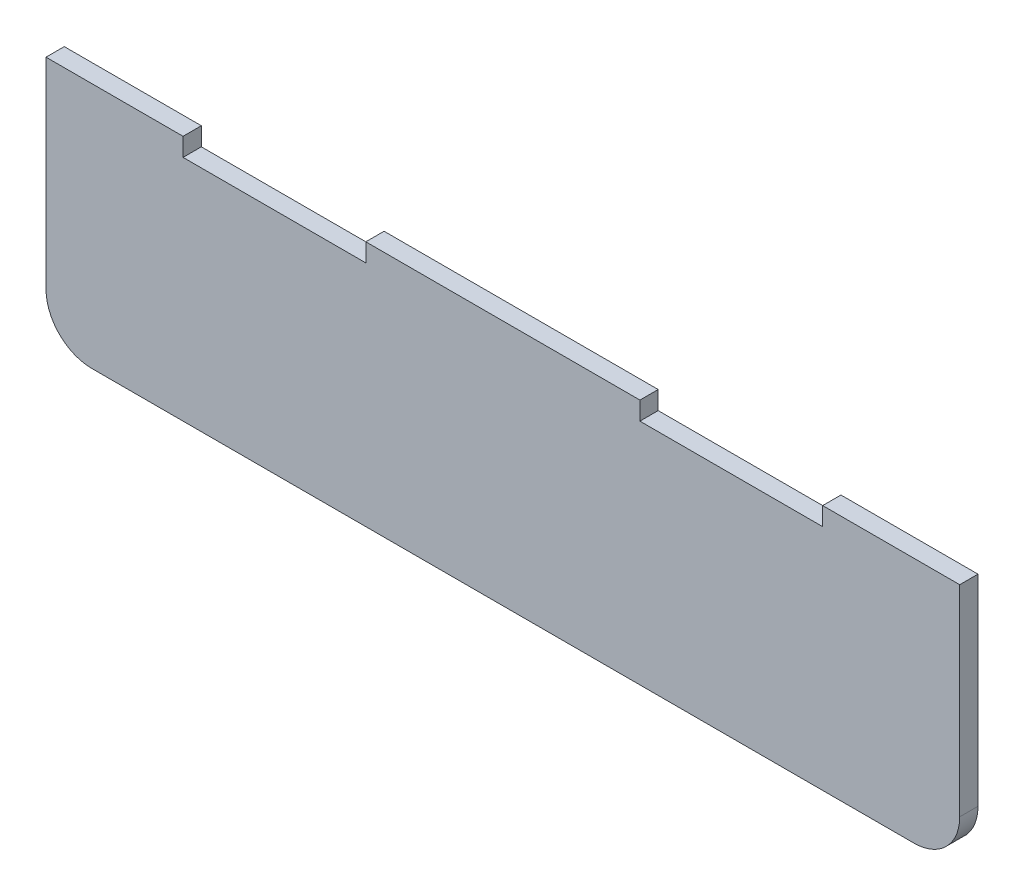
SolidWorks part; units mm, degrees
ref_plane "Front Plane" through (0, 0, 0) normal (0, 0, 1) x (1, 0, 0)
ref_plane "Top Plane" through (0, 0, 0) normal (0, 1, 0) x (1, 0, 0)
ref_plane "Right Plane" through (0, 0, 0) normal (1, 0, 0) x (0, 0, -1)
sketch "Sketch1" plane through (0, 0, 0) normal (0, 0, 1) x (1, 0, 0)
  line L0 (25, 25) -> (75, 25) construction
  line L1 (10, 0) -> (190, 0)
  line L2 (0, 10) -> (0, 50)
  line L3 (30, 50) -> (70, 50)
  line L4 (200, 10) -> (200, 50)
  line L5 (75, 25) -> (125, 25) construction
  line L6 (125, 25) -> (175, 25) construction
  line L7 (130, 50) -> (170, 50)
  line L9 (0, 50) -> (0, 54)
  line L10 (0, 54) -> (30, 54)
  line L11 (30, 50) -> (30, 54)
  line L13 (200, 50) -> (200, 54)
  line L14 (200, 54) -> (170, 54)
  line L15 (170, 50) -> (170, 54)
  line L17 (70, 50) -> (70, 54)
  line L18 (70, 54) -> (130, 54)
  line L19 (130, 50) -> (130, 54)
  arc A4 (190, 0) -> (200, 10) centre (190, 10) ccw
  arc A5 (10, 0) -> (0, 10) centre (10, 10) cw
  point P17 (0, 0)
  dimension "D6" = 10
  dimension "D1" = 200
  dimension "D2" = 50
  dimension "D4" = 25
  dimension "D5" = 25
  dimension "D7" = 4
  dimension "D8" = 4
  dimension "D9" = 4
  dimension "D10" = 40
  dimension "D11" = 40
  dimension "D12" = 30
  dimension "D13" = 50
extrude "Boss-Extrude1" add sketch "Sketch1" along normal blind 4
